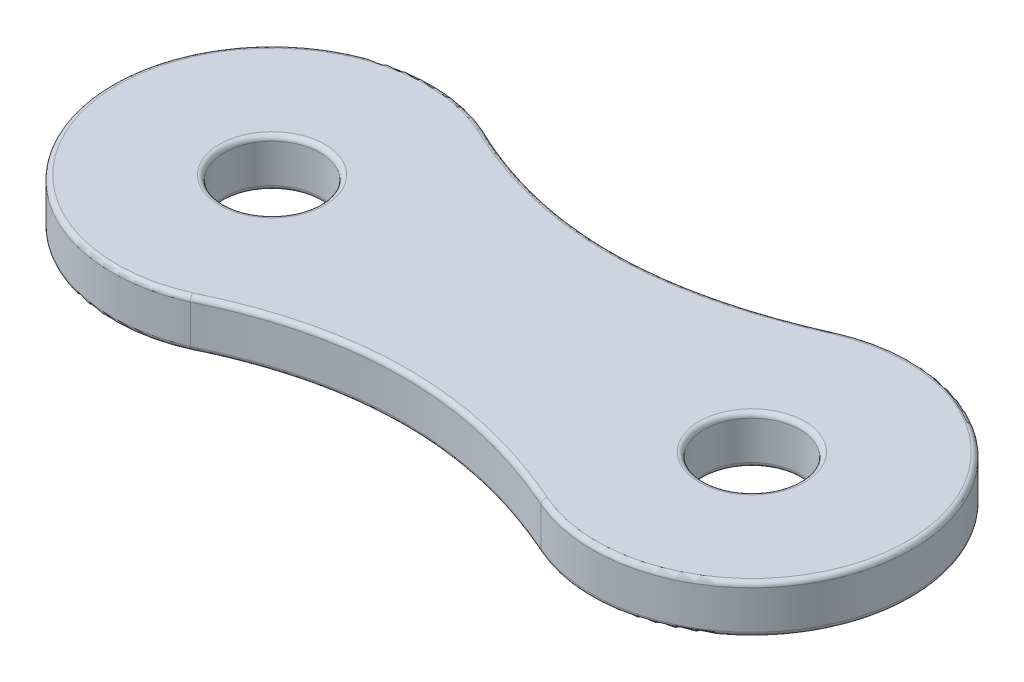
SolidWorks part; units mm, degrees
ref_plane "Front Plane" through (0, 0, 0) normal (0, 0, 1) x (1, 0, 0)
ref_plane "Top Plane" through (0, 0, 0) normal (0, 1, 0) x (1, 0, 0)
ref_plane "Right Plane" through (0, 0, 0) normal (1, 0, 0) x (0, 0, -1)
sketch "Sketch1" plane through (0, 0, 0) normal (0, 1, 0) x (1, 0, 0)
  line L1 (-1.25, 0.5) -> (1.25, 0.5) construction
  line L2 (-1.25, 0.5) -> (-1.25, -0.5) construction
  line L3 (-1.25, -0.5) -> (1.25, -0.5) construction
  line L4 (1.25, 0.5) -> (1.25, -0.5) construction
  line L5 (-1.25, 0.5) -> (1.25, -0.5) construction
  line L6 (-1.25, -0.5) -> (1.25, 0.5) construction
  point P0 (0, 0)
  dimension "D1" = 2.5
  dimension "D2" = 1
sketch "Sketch2" plane through (0, 0, 0) normal (0, 1, 0) x (1, 0, 0)
  line L0 (-1.25, 0.5) -> (-1.25, -0.5) construction
  line L1 (1.25, 0.5) -> (1.25, -0.5) construction
  line L2 (-0.75, 0) -> (0.75, 0) construction
  arc A0 (-0.5481, 0.4574) -> (-0.5481, -0.4574) centre (-0.75, 0) ccw
  arc A1 (0.5481, -0.4574) -> (0.5481, 0.4574) centre (0.75, 0) ccw
  circle A2 centre (-0.75, 0) radius 0.15
  circle A3 centre (0.75, 0) radius 0.15
  spline S0 degree 3 poles (-0.5481, 0.4574) (-0.161, 0.2696) (0.1963, 0.3021) (0.5481, 0.4574) knots 0 0 0 0 1 1 1 1
  spline S1 degree 3 poles (-0.5481, -0.4574) (-0.161, -0.2696) (0.1963, -0.3021) (0.5481, -0.4574) knots 0 0 0 0 1 1 1 1
  dimension "D1" = 1
  dimension "D2" = 0.3
extrude "Boss-Extrude1" add sketch "Sketch2" along normal blind 0.15
fillet "Fillet1" radius 0.015 12 edges at (0.75, 0, 0.15) (-0.75, 0, 0.15) (1.25, 0, 0) (-1.25, 0, 0) (0.75, 0.15, 0.15) (-1.25, 0.15, 0) (1.25, 0.15, 0) (-0.75, 0.15, 0.15)
